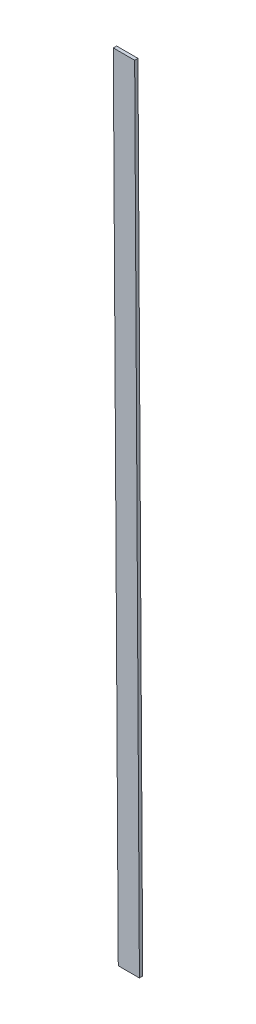
SolidWorks part; units mm, degrees
material "Balsa"
ref_plane "Front Plane" through (0, 0, 0) normal (0, 0, 1) x (1, 0, 0)
ref_plane "Top Plane" through (0, 0, 0) normal (0, 1, 0) x (1, 0, 0)
ref_plane "Right Plane" through (0, 0, 0) normal (1, 0, 0) x (0, 0, -1)
sketch "Sketch1" plane through (0, 0, 0) normal (0, 0, 1) x (1, 0, 0)
  line L0 (50.1892, -88.3495) -> (60.3492, -88.3495)
  line L1 (60.3492, -88.3495) -> (58.0702, 292.6609)
  line L2 (58.0702, 292.6609) -> (47.7983, 292.6609)
  line L3 (47.7983, 292.6609) -> (50.1892, -88.3495)
extrude "Boss-Extrude1" add sketch "Sketch1" along normal blind 1.5875
